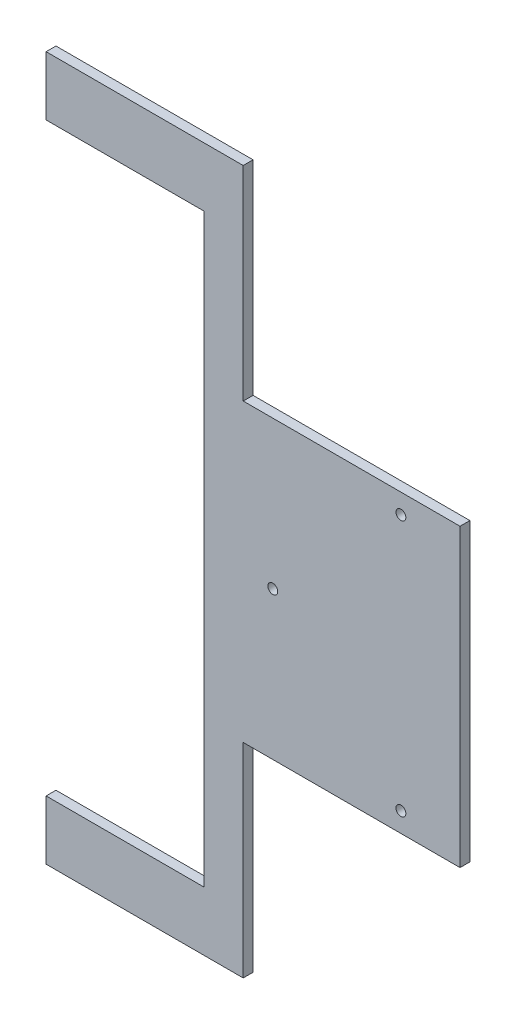
SolidWorks part; units mm, degrees
ref_plane "Front Plane" through (0, 0, 0) normal (0, 0, 1) x (1, 0, 0)
ref_plane "Top Plane" through (0, 0, 0) normal (0, 1, 0) x (1, 0, 0)
ref_plane "Right Plane" through (0, 0, 0) normal (1, 0, 0) x (0, 0, -1)
sketch "Sketch1" plane through (0, 0, 0) normal (0, 0, 1) x (1, 0, 0)
  line L0 (30.0007, 17.5455) -> (-37.4993, 17.5455) construction
  line L5 (-49.9993, 92.5455) -> (60.0007, 92.5455)
  line L6 (60.0007, 92.5455) -> (60.0007, -57.4545)
  line L8 (60.0007, -57.4545) -> (-49.9993, -57.4545)
  line L9 (-69.9993, -130.9545) -> (-69.9993, 166.0455)
  line L11 (-49.9993, -130.9545) -> (-49.9993, -57.4545)
  line L13 (-49.9993, 166.0455) -> (-49.9993, 92.5455)
  line L14 (-49.9993, 166.0455) -> (-49.9993, 196.0455)
  line L15 (-49.9993, 196.0455) -> (-149.9993, 196.0455)
  line L16 (-49.9993, -130.9545) -> (-49.9993, -160.9545)
  line L17 (-49.9993, -160.9545) -> (-149.9993, -160.9545)
  line L18 (-149.9993, -160.9545) -> (-149.9993, -130.9545)
  line L19 (-69.9993, 166.0455) -> (-149.9993, 166.0455)
  line L20 (-69.9993, -130.9545) -> (-149.9993, -130.9545)
  line L21 (-149.9993, 166.0455) -> (-149.9993, 196.0455)
  circle A7 centre (-34.9993, 17.5455) radius 2.5
  circle A10 centre (30.0007, -47.4545) radius 2.5
  circle A11 centre (30.0007, 82.5455) radius 2.5
  point P6 (-69.9993, 17.5455)
  point P18 (34.0007, 60.0455)
  point P21 (-34.9993, 17.5455)
  dimension "D2" = 73.5
  dimension "D3" = 20
  dimension "D4" = 150
  dimension "D5" = 297
  dimension "D6" = 5
  dimension "D7" = 73.5
  dimension "D8" = 20
  dimension "D9" = 5
  dimension "D10" = 5
extrude "Boss-Extrude1" add sketch "Sketch1" along normal blind 5
